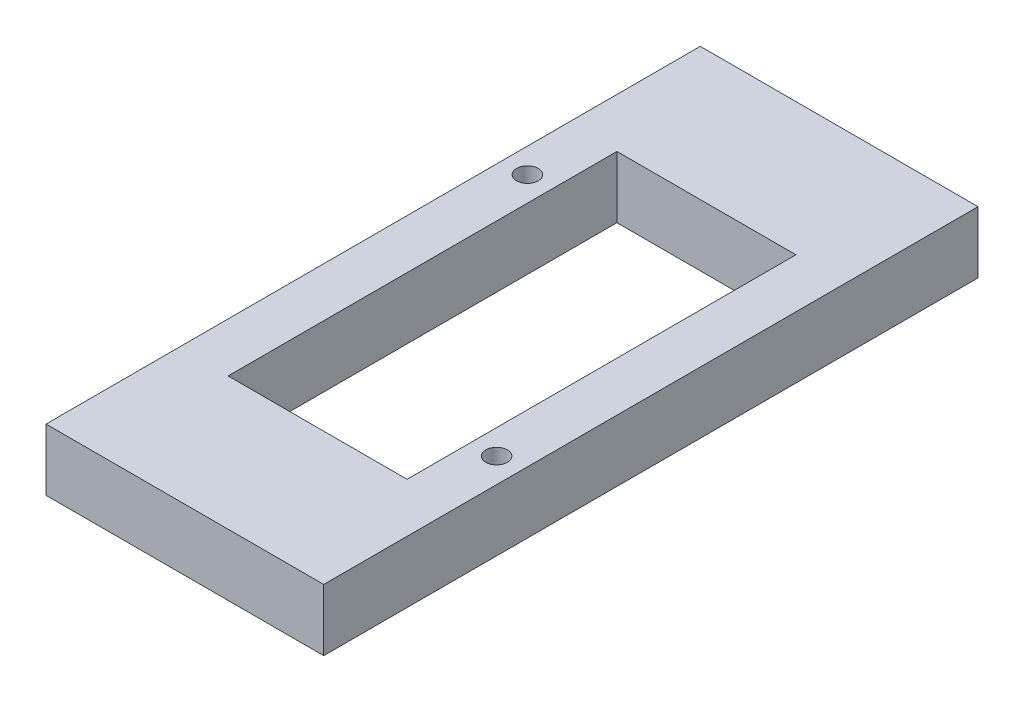
SolidWorks part; units mm, degrees
ref_plane "前视基准面" through (0, 0, 0) normal (0, 0, 1) x (1, 0, 0)
ref_plane "上视基准面" through (0, 0, 0) normal (0, 1, 0) x (1, 0, 0)
ref_plane "右视基准面" through (0, 0, 0) normal (1, 0, 0) x (0, 0, -1)
other "Configuration Table"
sketch "草图1" plane through (0, 0, 0) normal (0, 1, 0) x (1, 0, 0)
  line L1 (0, 0) -> (45, 0)
  line L2 (0, 0) -> (0, -106)
  line L3 (0, -106) -> (45, -106)
  line L4 (45, 0) -> (45, -106)
  line L5 (8, -21.5) -> (37, -21.5)
  line L6 (8, -21.5) -> (8, -84.5)
  line L7 (8, -84.5) -> (37, -84.5)
  line L8 (37, -21.5) -> (37, -84.5)
  circle A0 centre (4, -32) radius 1.75
  circle A1 centre (41, -74) radius 1.75
  dimension "D8" = 3.5
  dimension "D12" = 3.5
  dimension "D1" = 106
  dimension "D2" = 45
  dimension "D3" = 21.5
  dimension "D4" = 21.5
  dimension "D5" = 8
  dimension "D6" = 8
  dimension "D7" = 32
  dimension "D9" = 74
  dimension "D10" = 4
  dimension "D11" = 4
extrude "凸台-拉伸1" add sketch "草图1" along normal blind 10
ref_plane "基准面1" through (0, -15, 0) normal (0, 1, 0) x (1, 0, 0)
sketch "草图2" plane through (0, -15, 0) normal (0, 1, 0) x (1, 0, 0)
  line L0 (45, -106) -> (45, 0) construction
  line L1 (0, -106) -> (45, -106) construction
  circle A0 centre (22.5, -53) radius 3.3386
  dimension "D1" = 22.5
  dimension "D2" = 53
equation "\"D1@草图2\"=45/2"
equation "\"D2@草图2\"=\"D1@草图1\"/2"
